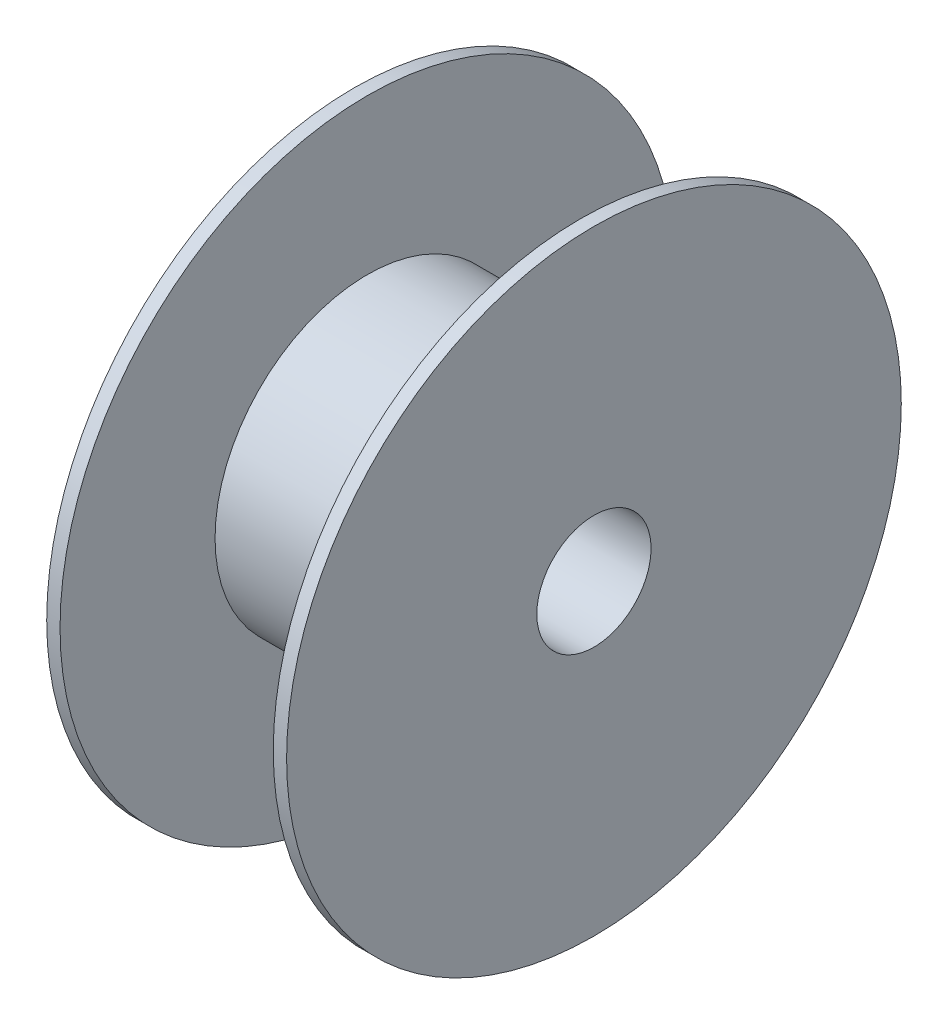
SolidWorks part; units mm, degrees
ref_plane "Front Plane" through (0, 0, 0) normal (0, 0, 1) x (1, 0, 0)
ref_plane "Top Plane" through (0, 0, 0) normal (0, 1, 0) x (1, 0, 0)
ref_plane "Right Plane" through (0, 0, 0) normal (1, 0, 0) x (0, 0, -1)
sketch "Sketch1" plane through (0, 0, 0) normal (0, 0, 1) x (1, 0, 0)
  line L0 (0, 0) -> (52.484, 0) construction
  line L1 (80, 19.05) -> (0, 19.05)
  line L4 (0, 19.05) -> (0, 102.5)
  line L5 (0, 102.5) -> (4.445, 102.5)
  line L6 (4.445, 102.5) -> (4.445, 50.8)
  line L7 (4.445, 50.8) -> (75.555, 50.8)
  line L8 (75.555, 50.8) -> (75.555, 102.5)
  line L9 (75.555, 102.5) -> (80, 102.5)
  line L10 (80, 102.5) -> (80, 19.05)
  dimension "D1" = 4.445
  dimension "D2" = 80
  dimension "D4" = 38.1
  dimension "D5" = 101.6
  dimension "D6" = 205
revolve "Revolve1" add sketch "Sketch1" angle 360 about L0
